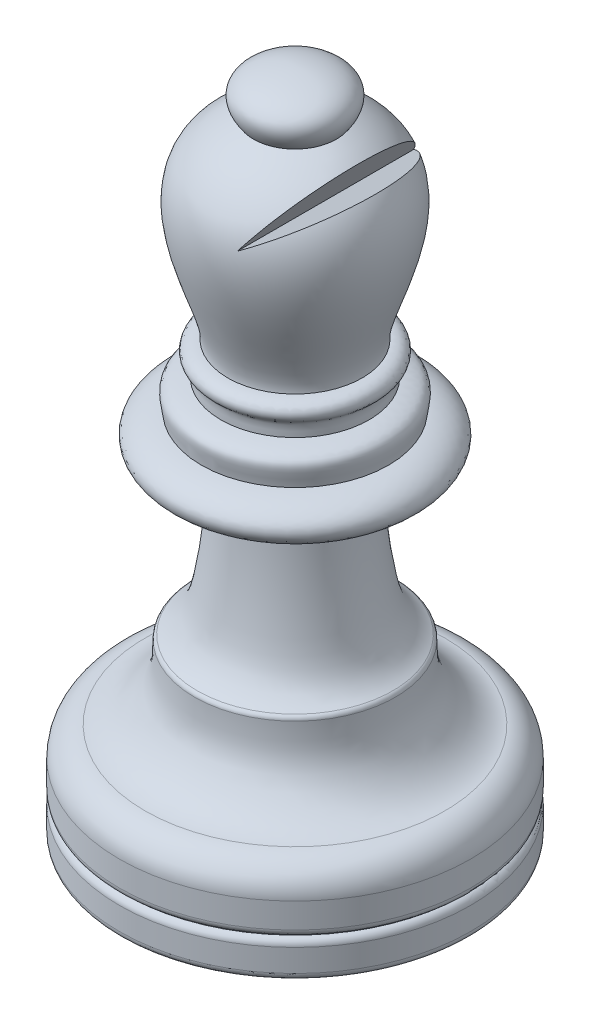
SolidWorks part; units mm, degrees
ref_plane "Front Plane" through (0, 0, 0) normal (0, 0, 1) x (1, 0, 0)
ref_plane "Top Plane" through (0, 0, 0) normal (0, 1, 0) x (1, 0, 0)
ref_plane "Right Plane" through (0, 0, 0) normal (1, 0, 0) x (0, 0, -1)
sketch "Sketch1" plane through (0, 0, 0) normal (0, 0, 1) x (1, 0, 0)
  line L0 (0, 0) -> (0, 95.25) construction
  dimension "D1" = 95.25
sketch "Sketch2" plane through (0, 0, 0) normal (0, 0, 1) x (1, 0, 0)
  line L1 (0, 0) -> (0, 10.0349)
  line L3 (0, 0) -> (-17.018, 0)
  line L4 (-17.78, 0.762) -> (-17.78, 3.048)
  line L5 (-17.78, 4.572) -> (-17.78, 7.112)
  line L8 (170.8832, 3.81) -> (0, 3.81) construction
  line L9 (-17.272, 3.8536) -> (-17.272, 3.7664)
  line L16 (-15.1743, 10.0349) -> (0, 10.0349)
  arc A4 (-15.1743, 10.0349) -> (-17.78, 7.112) centre (-14.8378, 7.112) ccw
  arc A5 (-17.78, 4.572) -> (-17.272, 3.8536) centre (-17.018, 4.572) ccw
  arc A6 (-17.272, 3.7664) -> (-17.78, 3.048) centre (-17.018, 3.048) ccw
  arc A7 (-17.018, 0) -> (-17.78, 0.762) centre (-17.018, 0.762) cw
  dimension "D5" = 0.762
  dimension "D6" = 0.762
  dimension "D13" = 17.78
  dimension "D11" = 3.81
  dimension "D12" = 3.302
  dimension "D14" = 0.508
revolve "Revolve2" add sketch "Sketch2" angle 360 about L1
sketch "Sketch3" plane through (0, 0, 0) normal (0, 0, 1) x (1, 0, 0)
  line L0 (-6.3356, 34.5848) -> (-6.3356, 31.1142) construction
  line L1 (-7.5026, 41.1644) -> (-7.5026, 39.704) construction
  line L2 (-5.0964, 43.8223) -> (-8.5116, 43.8223) construction
  line L3 (0, 0) -> (0, 95.25) construction
  line L4 (2.2726, 67.6699) -> (-2.2726, 67.6699) construction
  line L5 (0, 67.6699) -> (0, 10.0349)
  line L6 (15.1743, 10.0349) -> (-15.1743, 10.0349) construction
  line L7 (0, 10.0349) -> (-15.1743, 10.0349)
  arc A0 (-10.1658, 17.505) -> (-9.9089, 17.9426) centre (-9.6578, 17.501) cw
  arc A1 (-15.1743, 10.0349) -> (-17.78, 7.112) centre (-14.8378, 7.112) ccw construction
  spline S0 degree 3 poles (-15.1743, 10.0349) (-13.3161, 10.2489) (-10.3593, 13.0902) (-10.181, 15.5949) (-10.1658, 17.505) knots 0 0 0 0 0.538934 0.976645 0.976645 0.976645 0.976645
  spline S1 degree 3 poles (-9.9089, 17.9426) (-8.1872, 18.9216) (-7.2017, 22.0085) (-6.3356, 28.9385) (-6.3356, 32.8495) knots 0.034064 0.034064 0.034064 0.034064 0.517032 1 1 1 1
  spline S2 degree 3 poles (-6.3356, 32.8495) (-14.7005, 33.3538) (-13.5516, 37.1083) (-9.4768, 37.5095) knots 0 0 0 0 1 1 1 1
  spline S3 degree 3 poles (-9.4768, 37.5095) (-9.6589, 39.3112) (-10.4091, 40.1261) (-7.5026, 40.4959) knots 0 0 0 0 1 1 1 1
  spline S4 degree 3 poles (-7.5026, 40.4959) (-7.5026, 41.249) (-7.4502, 41.8732) (-8.5782, 42.5723) (-8.3429, 43.8223) (-6.804, 43.8223) knots 0 0 0 0 0.324588 0.424588 1 1 1 1
  spline S5 degree 3 poles (-6.804, 43.8223) (-6.2809, 47.5213) (-14.9076, 58.9286) (-4.2019, 63.4648) knots 0 0 0 0 1 1 1 1
  spline S6 degree 3 poles (-4.2019, 63.4648) (-6.784, 66.8839) (-1.8938, 67.6699) (0, 67.6699) knots 0 0 0 0 1 1 1 1
  dimension "D1" = 0.508
revolve "Revolve3" add sketch "Sketch3" angle 360 about L5
sketch "Sketch4" plane through (0, 0, 0) normal (0, 0, 1) x (1, 0, 0)
  line L0 (12.3193, 71.1459) -> (3.096, 57.5573)
  line L1 (3.096, 57.5573) -> (16.9662, 65.9358)
  line L2 (16.9662, 65.9358) -> (12.3193, 71.1459)
extrude "Cut-Extrude1" cut sketch "Sketch4" against normal through all and the other way through all
move or copy body "Body-Move/Copy1" [suppressed] bodies to move or copy 107 copy no rotation origin (0, 0, 0) rotation axis (0, 1, 0) rotation angle 180
